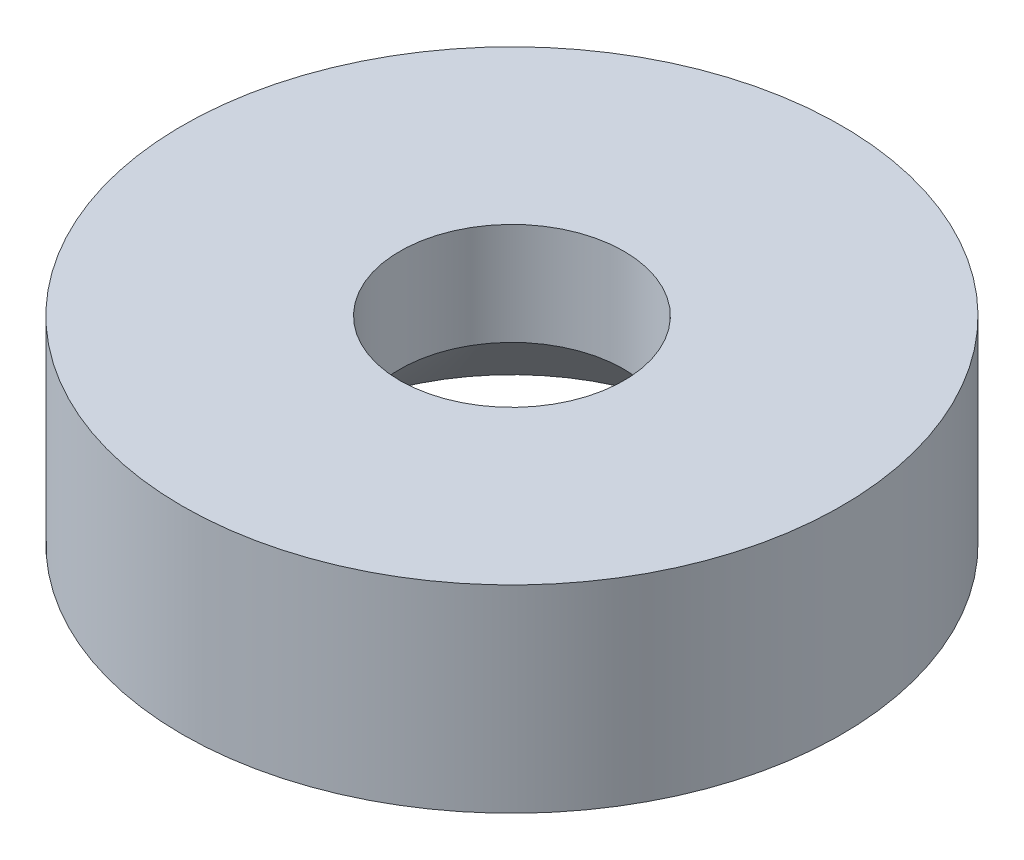
SolidWorks part; units mm, degrees
material "Nickel"
ref_plane "Front Plane" through (0, 0, 0) normal (0, 0, 1) x (1, 0, 0)
ref_plane "Top Plane" through (0, 0, 0) normal (0, 1, 0) x (1, 0, 0)
ref_plane "Right Plane" through (0, 0, 0) normal (1, 0, 0) x (0, 0, -1)
sketch "Sketch1" plane through (0, 0, 0) normal (0, 1, 0) x (1, 0, 0)
  circle A0 centre (0.4758, -0.9241) radius 5
  dimension "D2" = 10
extrude "Boss-Extrude1" add sketch "Sketch1" along normal blind 3
hole_wizard "CSK for M3 Flat Head Machine Screw1" positions "3DSketch2" profile "Sketch3" countersink size "M3" standard "ANSI Metric" end condition through all
sketch3d "3DSketch2"
  line L0 (0.4758, 0, 0.9241) -> (-3.0597, 0, 4.4597) construction
  line L1 (0.4758, 3, 0.9241) -> (0.4758, 0, 0.9241) construction
  line L2 (0.4758, 0, 0.9241) -> (-3.0597, 0, -2.6114) construction
  circle A0 centre (0.4758, 0, 0.9241) radius 5 construction
  point P0 (0.4758, 0, 0.9241)
  point P9 (0.4758, 5, 0.9241)
sketch "Sketch3" plane through (0.4758, 0, 0.9241) normal (1, 0, 0) x (0, 0, -1)
  line L0 (0, 0) -> (0, 3)
  line L1 (0, 3) -> (1.7, 3)
  line L2 (1.7, 3) -> (1.7, 1.45)
  line L3 (1.7, 1.45) -> (3.15, 0)
  line L5 (3.15, 0) -> (0, 0)
  line L6 (-1.7, 1.45) -> (-3.15, 0) construction
  line L11 (0, -6.35) -> (0, 107.95) construction
  dimension "Thru Hole Dia." = 3.4
  dimension "Thru Hole Depth" = 3
  dimension "Near C'Sink Dia." = 6.3
  dimension "Near C'Sink Angle" = 90
